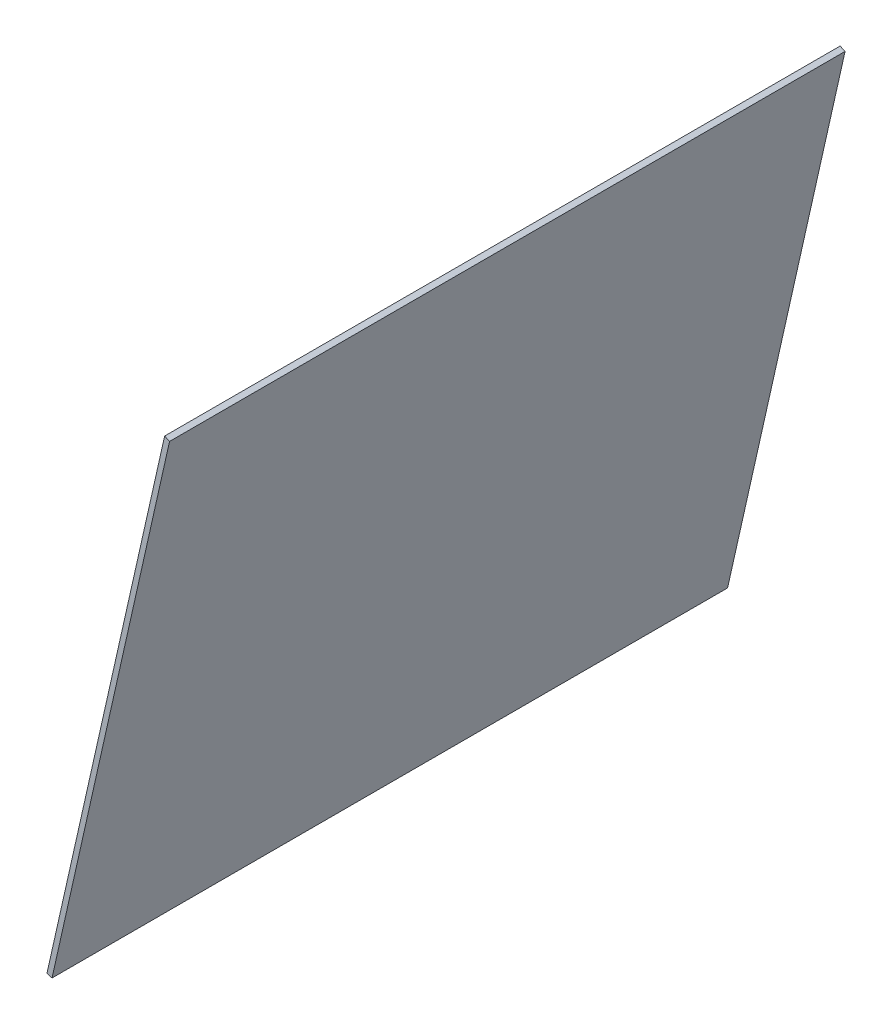
SolidWorks part; units mm, degrees
material "Pine"
ref_plane "Front Plane" through (0, 0, 0) normal (0, 0, 1) x (1, 0, 0)
ref_plane "Top Plane" through (0, 0, 0) normal (0, 1, 0) x (1, 0, 0)
ref_plane "Right Plane" through (0, 0, 0) normal (1, 0, 0) x (0, 0, -1)
sketch "Sketch1" plane through (0, 0, 0) normal (0, 0, 1) x (1, 0, 0)
  line L0 (-110.6032, 958.6365) -> (-252.2205, 327.7957)
  line L12 (-104.6977, 955.9522) -> (-246.0839, 326.1409)
  line L13 (-252.2205, 327.7957) -> (-246.0839, 326.1409)
  line L26 (-110.6032, 958.6365) -> (-104.6977, 955.9522)
  dimension "D1" = 78.209
extrude "Boss-Extrude1" add sketch "Sketch1" along normal blind 812.8
